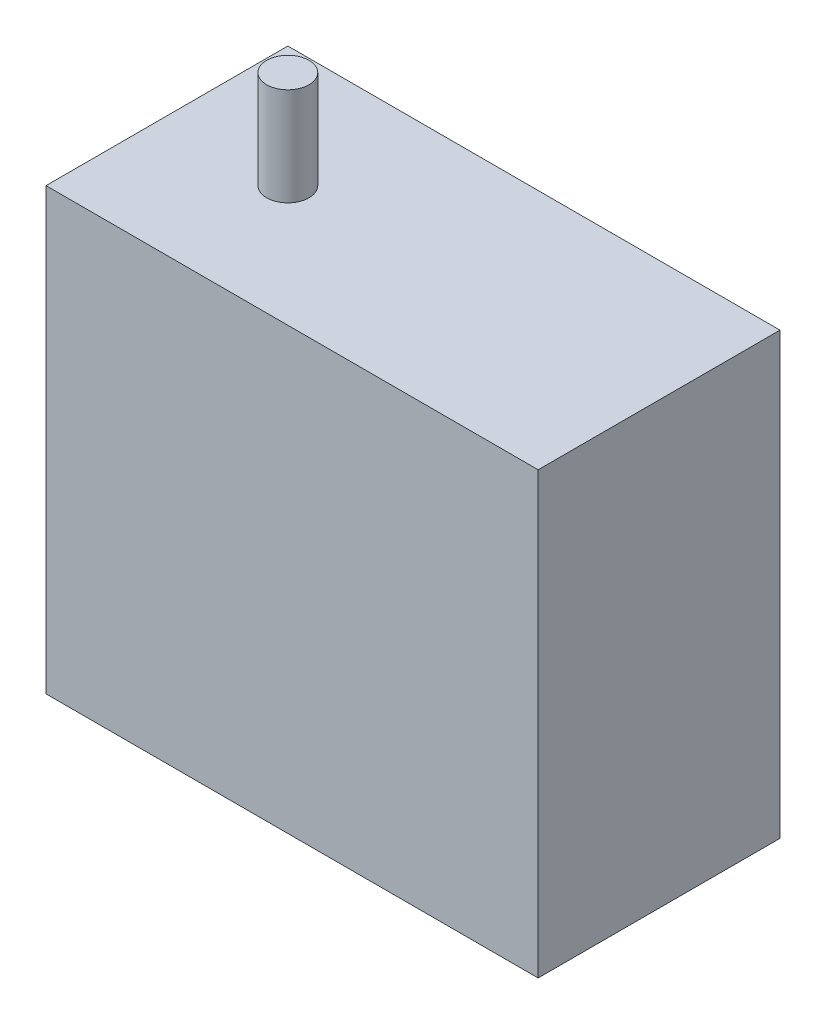
SolidWorks part; units mm, degrees
ref_plane "Front" through (0, 0, 0) normal (0, 0, 1) x (1, 0, 0)
ref_plane "Top" through (0, 0, 0) normal (0, 1, 0) x (1, 0, 0)
ref_plane "Right" through (0, 0, 0) normal (1, 0, 0) x (0, 0, -1)
sketch "Sketch1" plane through (0, 0, 0) normal (0, 1, 0) x (1, 0, 0)
  line L1 (-20.35, 10) -> (20.35, 10)
  line L2 (-20.35, 10) -> (-20.35, -10)
  line L3 (-20.35, -10) -> (20.35, -10)
  line L4 (20.35, 10) -> (20.35, -10)
  line L5 (-20.35, 10) -> (20.35, -10) construction
  line L6 (-20.35, -10) -> (20.35, 10) construction
  point P0 (0, 0)
  dimension "D1" = 20
  dimension "D2" = 40.7
extrude "Boss-Extrude1" add sketch "Sketch1" along normal blind 36.4
sketch "Sketch2" plane through (0, 36.4, 0) normal (0, 1, 0) x (1, 0, 0)
  line L0 (-20.35, 0) -> (-10.35, 0) construction
  line L1 (-20.35, 10) -> (-20.35, -10) construction
  circle A0 centre (-10.35, 0) radius 1.75
  dimension "D2" = 3.5
  dimension "D1" = 10
extrude "Boss-Extrude2" add sketch "Sketch2" along normal blind 8.1
